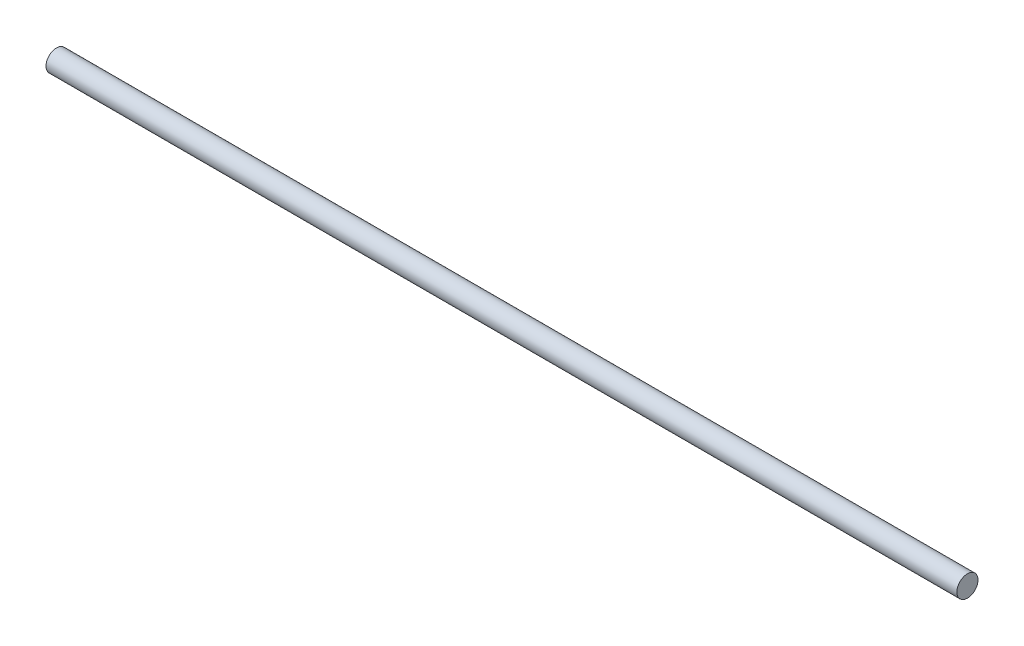
SolidWorks part; units mm, degrees
material "Hexcel AS4C (3000 Filaments)"
ref_plane "Front Plane" through (0, 0, 0) normal (0, 0, 1) x (1, 0, 0)
ref_plane "Top Plane" through (0, 0, 0) normal (0, 1, 0) x (1, 0, 0)
ref_plane "Right Plane" through (0, 0, 0) normal (1, 0, 0) x (0, 0, -1)
sketch "Sketch1" plane through (0, 0, 0) normal (1, 0, 0) x (0, 0, -1)
  circle A0 centre (0, 0) radius 5
  dimension "D1" = 10
extrude "Boss-Extrude1" add sketch "Sketch1" along normal mid plane 431
